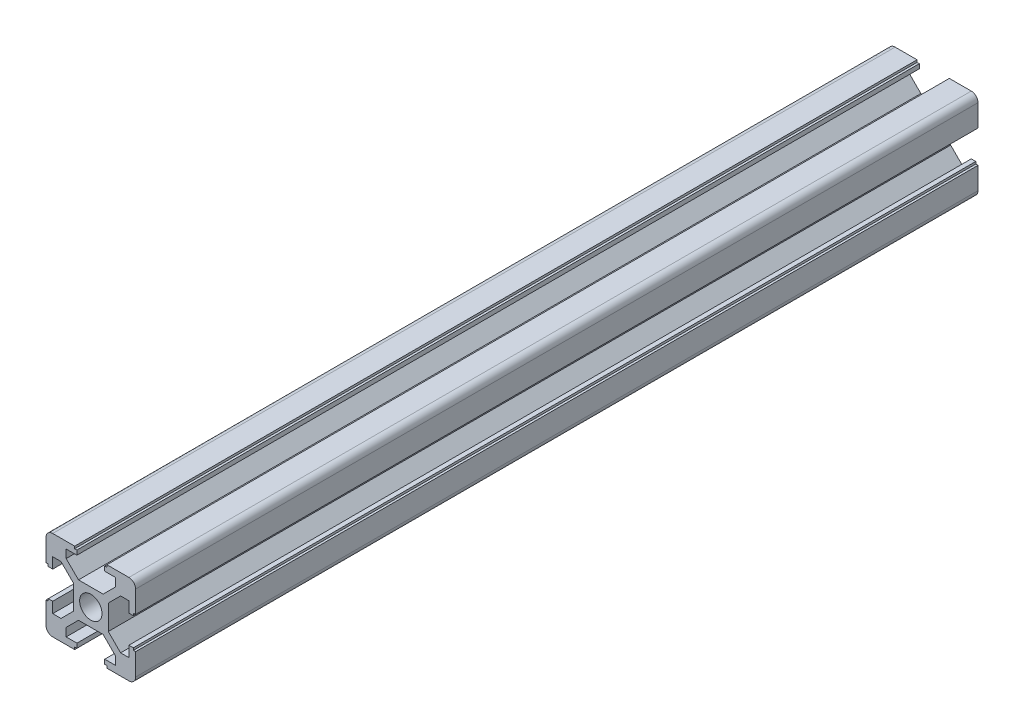
SolidWorks part; units mm, degrees
ref_plane "Plane1" through (0, 0, 0) normal (0, 0, 1) x (1, 0, 0)
ref_plane "Plane2" through (0, 0, 0) normal (0, 1, 0) x (1, 0, 0)
ref_plane "Plane3" through (0, 0, 0) normal (1, 0, 0) x (0, 0, -1)
sketch "Sketch1" plane through (0, 0, 0) normal (0, 0, 1) x (1, 0, 0)
  line L0 (-3.6, 10) -> (-3.6, 9.5)
  line L1 (-3.6, 9.5) -> (-3.1, 9.5)
  line L2 (-3.1, 9.5) -> (-3.1, 8.5)
  line L3 (-3.1, 8.5) -> (-5.5, 8.5)
  line L4 (-8.5, -10) -> (-3.6, -10)
  line L5 (-10, -8.5) -> (-10, -3.6)
  line L6 (8.5, 10) -> (3.6, 10)
  line L7 (10, 8.5) -> (10, 3.6)
  line L8 (0, 14.8756) -> (0, 0) construction
  line L9 (0, 0) -> (14.1675, 0) construction
  line L10 (-5.5, 8.5) -> (-5.5, 6.65)
  line L11 (-5.5, 6.65) -> (-2.75, 3.9)
  line L12 (-2.75, 3.9) -> (2.75, 3.9)
  line L13 (5.5, 6.65) -> (2.75, 3.9)
  line L14 (5.5, 8.5) -> (5.5, 6.65)
  line L15 (3.1, 8.5) -> (5.5, 8.5)
  line L16 (3.1, 9.5) -> (3.1, 8.5)
  line L17 (3.6, 9.5) -> (3.1, 9.5)
  line L18 (3.6, 10) -> (3.6, 9.5)
  line L19 (-3.6, 10) -> (-8.5, 10)
  line L20 (10, 3.6) -> (9.5, 3.6)
  line L21 (9.5, 3.6) -> (9.5, 3.1)
  line L22 (9.5, 3.1) -> (8.5, 3.1)
  line L23 (8.5, 3.1) -> (8.5, 5.5)
  line L24 (8.5, 5.5) -> (6.65, 5.5)
  line L25 (6.65, 5.5) -> (3.9, 2.75)
  line L26 (3.9, 2.75) -> (3.9, -2.75)
  line L27 (6.65, -5.5) -> (3.9, -2.75)
  line L28 (8.5, -5.5) -> (6.65, -5.5)
  line L29 (8.5, -3.1) -> (8.5, -5.5)
  line L30 (9.5, -3.1) -> (8.5, -3.1)
  line L31 (9.5, -3.6) -> (9.5, -3.1)
  line L32 (10, -3.6) -> (9.5, -3.6)
  line L33 (3.6, -10) -> (3.6, -9.5)
  line L34 (3.6, -9.5) -> (3.1, -9.5)
  line L35 (3.1, -9.5) -> (3.1, -8.5)
  line L36 (3.1, -8.5) -> (5.5, -8.5)
  line L37 (5.5, -8.5) -> (5.5, -6.65)
  line L38 (5.5, -6.65) -> (2.75, -3.9)
  line L39 (2.75, -3.9) -> (-2.75, -3.9)
  line L40 (-5.5, -6.65) -> (-2.75, -3.9)
  line L41 (-5.5, -8.5) -> (-5.5, -6.65)
  line L42 (-3.1, -8.5) -> (-5.5, -8.5)
  line L43 (-3.1, -9.5) -> (-3.1, -8.5)
  line L44 (-3.6, -9.5) -> (-3.1, -9.5)
  line L45 (-3.6, -10) -> (-3.6, -9.5)
  line L46 (-10, -3.6) -> (-9.5, -3.6)
  line L47 (-9.5, -3.6) -> (-9.5, -3.1)
  line L48 (-9.5, -3.1) -> (-8.5, -3.1)
  line L49 (-8.5, -3.1) -> (-8.5, -5.5)
  line L50 (-8.5, -5.5) -> (-6.65, -5.5)
  line L51 (-6.65, -5.5) -> (-3.9, -2.75)
  line L52 (-3.9, -2.75) -> (-3.9, 2.75)
  line L53 (-6.65, 5.5) -> (-3.9, 2.75)
  line L54 (-8.5, 5.5) -> (-6.65, 5.5)
  line L55 (-8.5, 3.1) -> (-8.5, 5.5)
  line L56 (-9.5, 3.1) -> (-8.5, 3.1)
  line L57 (-9.5, 3.6) -> (-9.5, 3.1)
  line L58 (-10, 3.6) -> (-9.5, 3.6)
  line L59 (3.6, -10) -> (8.5, -10)
  line L60 (-10, 3.6) -> (-10, 8.5)
  line L61 (10, -3.6) -> (10, -8.5)
  circle A0 centre (0, 0) radius 2.5
  arc A1 (-10, 8.5) -> (-8.5, 10) centre (-8.5, 8.5) cw
  arc A2 (10, 8.5) -> (8.5, 10) centre (8.5, 8.5) ccw
  arc A3 (-8.5, -10) -> (-10, -8.5) centre (-8.5, -8.5) cw
  arc A4 (8.5, -10) -> (10, -8.5) centre (8.5, -8.5) ccw
  point P0 (-10, 0)
  point P1 (10, 0)
  point P2 (0, 10)
  point P3 (0, -10)
  point P4 (0, 0)
  point P5 (-10, -10)
  point P6 (10, -10)
  point P7 (10, 10)
  point P8 (-10, 10)
  point P36 (-10, 10)
  point P39 (10, 10)
extrude "凸台-拉伸1" add sketch "Sketch1" along normal blind 188
sketch "草图1" plane through (0, 3.9, 0) normal (0, 1, 0) x (1, 0, 0)
  line L0 (2.75, 0) -> (-2.75, 0) construction
  line L1 (2.75, -188) -> (-2.75, -188) construction
  circle A0 centre (0, -32) radius 2.2
  circle A1 centre (0, -56) radius 2.2
  circle A3 centre (0, -106) radius 2.2
  circle A4 centre (0, -132) radius 2.2
  circle A5 centre (0, -156) radius 2.2
  circle A6 centre (0, -82) radius 2.2
  point P0 (0, -32)
  point P3 (0, -56)
  point P6 (0, -82)
  point P9 (0, -106)
  point P10 (0, -132)
  point P11 (0, -156)
  dimension "D2" = 24
  dimension "D3" = 26
  dimension "D5" = 26
  dimension "D7" = 32
  dimension "D1" = 32
  dimension "D4" = 24
  dimension "D6" = 24
extrude "切除-拉伸1" cut sketch "草图1" against normal through all
